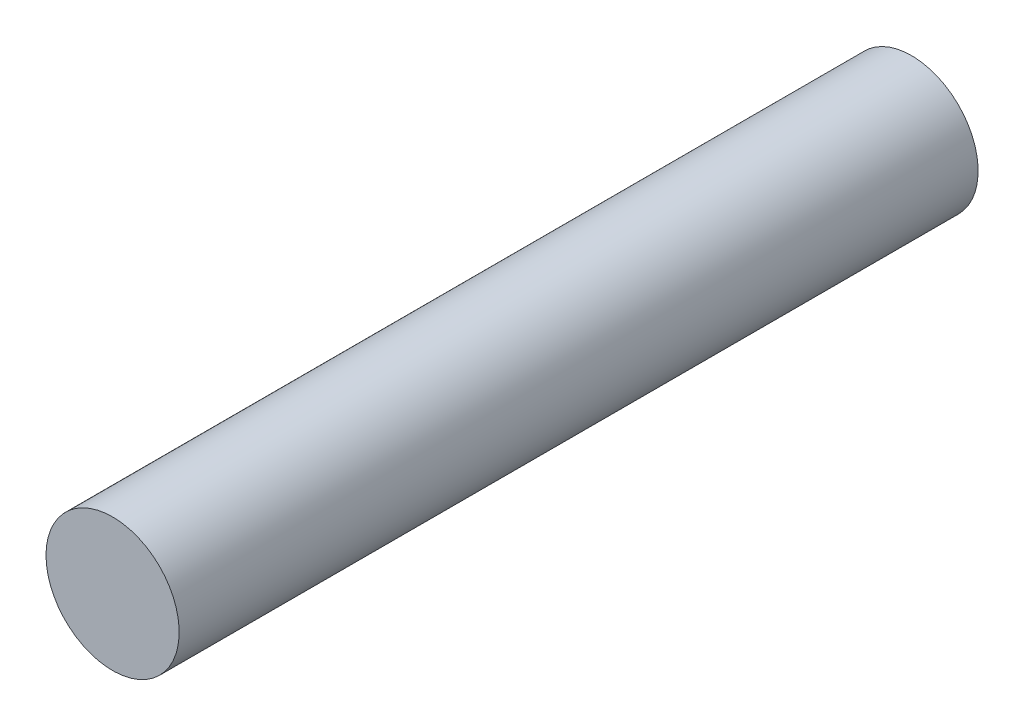
SolidWorks part; units mm, degrees
material "Plain Carbon Steel"
ref_plane "Front Plane" through (0, 0, 0) normal (0, 0, 1) x (1, 0, 0)
ref_plane "Top Plane" through (0, 0, 0) normal (0, 1, 0) x (1, 0, 0)
ref_plane "Right Plane" through (0, 0, 0) normal (1, 0, 0) x (0, 0, -1)
sketch "Sketch1" plane through (0, 0, 0) normal (0, 0, 1) x (1, 0, 0)
  circle A0 centre (0, 0) radius 6.35
  dimension "D1" = 12.7
extrude "Boss-Extrude1" add sketch "Sketch1" along normal blind 76.2
